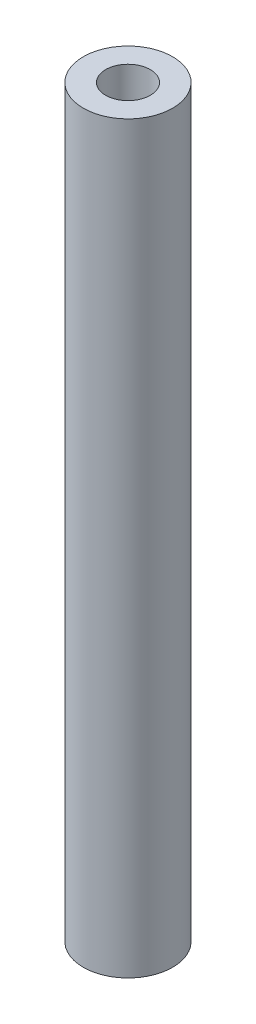
SolidWorks part; units mm, degrees
ref_plane "前视基准面" through (0, 0, 0) normal (0, 0, 1) x (1, 0, 0)
ref_plane "上视基准面" through (0, 0, 0) normal (0, 1, 0) x (1, 0, 0)
ref_plane "右视基准面" through (0, 0, 0) normal (1, 0, 0) x (0, 0, -1)
sketch "草图1" plane through (0, 0, 0) normal (0, 1, 0) x (1, 0, 0)
  circle A0 centre (0, 0) radius 1.5
  circle A1 centre (0, 0) radius 3
extrude "凸台-拉伸1" add sketch "草图1" along normal blind 50
